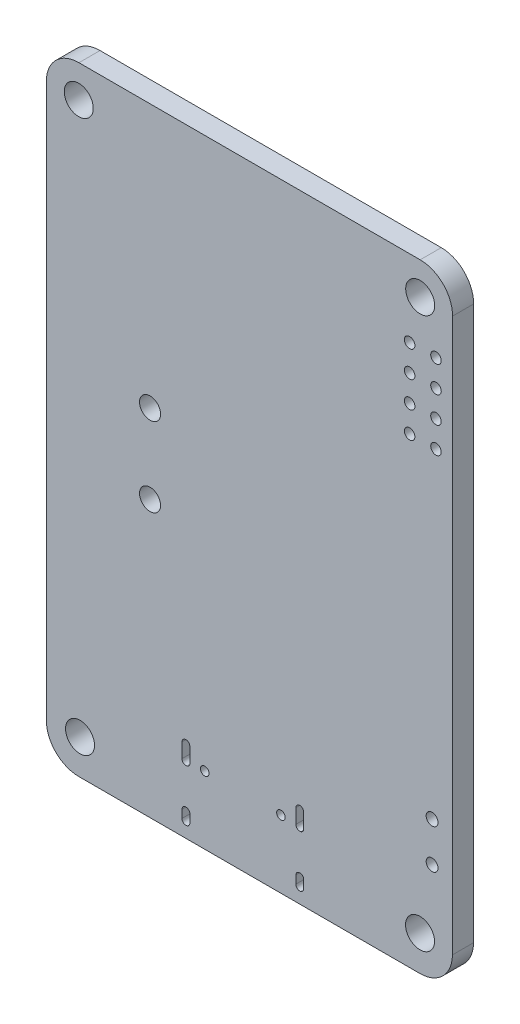
SolidWorks part; units mm, degrees
ref_plane "前视基准面" through (0, 0, 0) normal (0, 0, 1) x (1, 0, 0)
ref_plane "上视基准面" through (0, 0, 0) normal (0, 1, 0) x (1, 0, 0)
ref_plane "右视基准面" through (0, 0, 0) normal (1, 0, 0) x (0, 0, -1)
ref_plane "基准面1" through (0, 0, 0) normal (0, 0, -1) x (-1, 0, 0)
sketch "草图1" plane through (0, 0, 0) normal (0, 0, -1) x (-1, 0, 0)
  line L0 (-28.9242, 0.0029) -> (-3.03, 0.0047)
  line L1 (-0.5829, 2.4777) -> (-0.5817, 44.4687)
  line L2 (-3.0546, 46.9259) -> (-28.9511, 46.9201)
  line L3 (-31.4082, 44.4471) -> (-31.3971, 2.46)
  line L4 (-19.514, 1.765) -> (-19.514, 1.165)
  line L5 (-20.114, 1.165) -> (-20.114, 1.765)
  line L6 (-19.514, 6.195) -> (-19.514, 5.095)
  line L7 (-20.114, 5.095) -> (-20.114, 6.195)
  line L8 (-10.874, 1.765) -> (-10.874, 1.165)
  line L9 (-11.474, 1.165) -> (-11.474, 1.765)
  line L10 (-10.874, 6.195) -> (-10.874, 5.095)
  line L11 (-11.474, 5.095) -> (-11.474, 6.195)
  arc A0 (-3.03, 0.0047) -> (-0.5829, 2.4777) centre (-3.04, 2.4618) ccw
  arc A1 (-0.5817, 44.4687) -> (-3.0546, 46.9259) centre (-3.0388, 44.4688) ccw
  arc A2 (-28.9511, 46.9201) -> (-31.4082, 44.4471) centre (-28.9511, 44.463) ccw
  arc A3 (-31.3971, 2.46) -> (-28.9242, 0.0029) centre (-28.94, 2.46) ccw
  circle A4 centre (-28.94, 2.6629) radius 1.1
  circle A5 centre (-29.855, 7.61) radius 0.45
  circle A6 centre (-29.855, 10.61) radius 0.45
  arc A7 (-20.114, 1.765) -> (-19.514, 1.765) centre (-19.814, 1.765) cw
  arc A8 (-19.514, 1.165) -> (-20.114, 1.165) centre (-19.814, 1.165) cw
  arc A9 (-20.114, 6.195) -> (-19.514, 6.195) centre (-19.814, 6.195) cw
  arc A10 (-19.514, 5.095) -> (-20.114, 5.095) centre (-19.814, 5.095) cw
  circle A11 centre (-18.384, 5.145) radius 0.325
  arc A12 (-11.474, 1.765) -> (-10.874, 1.765) centre (-11.174, 1.765) cw
  arc A13 (-10.874, 1.165) -> (-11.474, 1.165) centre (-11.174, 1.165) cw
  circle A14 centre (-12.604, 5.145) radius 0.325
  arc A15 (-11.474, 6.195) -> (-10.874, 6.195) centre (-11.174, 6.195) cw
  arc A16 (-10.874, 5.095) -> (-11.474, 5.095) centre (-11.174, 5.095) cw
  circle A17 centre (-3.137, 2.65) radius 1.1
  circle A18 centre (-8.45, 20.925) radius 0.8
  circle A19 centre (-30.15, 35.08) radius 0.4
  circle A20 centre (-30.15, 37.08) radius 0.4
  circle A21 centre (-28.15, 35.08) radius 0.4
  circle A22 centre (-28.15, 37.08) radius 0.4
  circle A23 centre (-30.15, 39.08) radius 0.4
  circle A24 centre (-28.15, 39.08) radius 0.4
  circle A25 centre (-30.15, 41.08) radius 0.4
  circle A26 centre (-28.15, 41.08) radius 0.4
  circle A27 centre (-28.9511, 44.4629) radius 1.1
  circle A28 centre (-8.45, 26.925) radius 0.8
  circle A29 centre (-3.0388, 44.4688) radius 1.1
extrude "凸台-拉伸1" add sketch "草图1" against normal blind 1.6
sketch "草图3" plane through (0, 0, 1.6) normal (0, 0, 1) x (1, 0, 0)
  line L0 (15.9904, 46.9227) -> (15.9904, 0.0038)
  line L1 (31.4026, 0.0038) -> (0.5782, 0.0038)
  line L2 (31.4026, 0.0038) -> (31.4026, 46.9227)
  line L3 (31.4026, 46.9227) -> (0.5782, 46.9227)
  line L4 (0.5782, 0.0038) -> (0.5782, 46.9227)
  line L5 (31.4026, 23.4633) -> (0.5782, 23.4633)
ref_point "点3"
ref_plane "基准面5" through (15.9904, 23.4633, 1.6) normal (-1, 0, 0) x (0, 0, 1)
ref_plane "基准面6" through (15.9904, 23.4633, 1.6) normal (0, -1, 0) x (-1, 0, 0)
